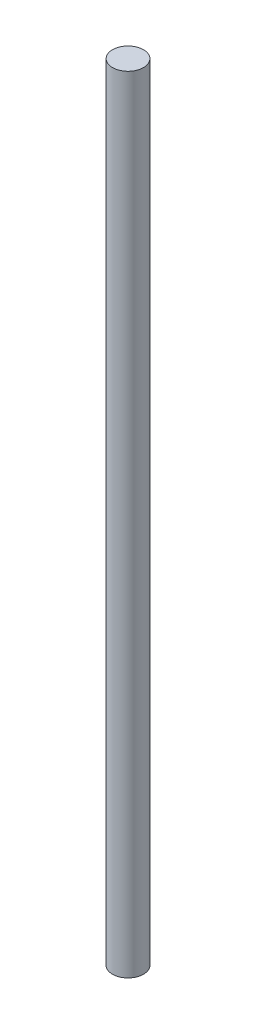
SolidWorks part; units mm, degrees
ref_plane "Front Plane" through (0, 0, 0) normal (0, 0, 1) x (1, 0, 0)
ref_plane "Top Plane" through (0, 0, 0) normal (0, 1, 0) x (1, 0, 0)
ref_plane "Right Plane" through (0, 0, 0) normal (1, 0, 0) x (0, 0, -1)
sketch "Sketch2" plane through (0, 0, 0) normal (0, 1, 0) x (1, 0, 0)
  circle A0 centre (0, 0) radius 4.7625
  dimension "D1" = 9.525
extrude "Boss-Extrude1" add sketch "Sketch2" along normal blind 241.3
